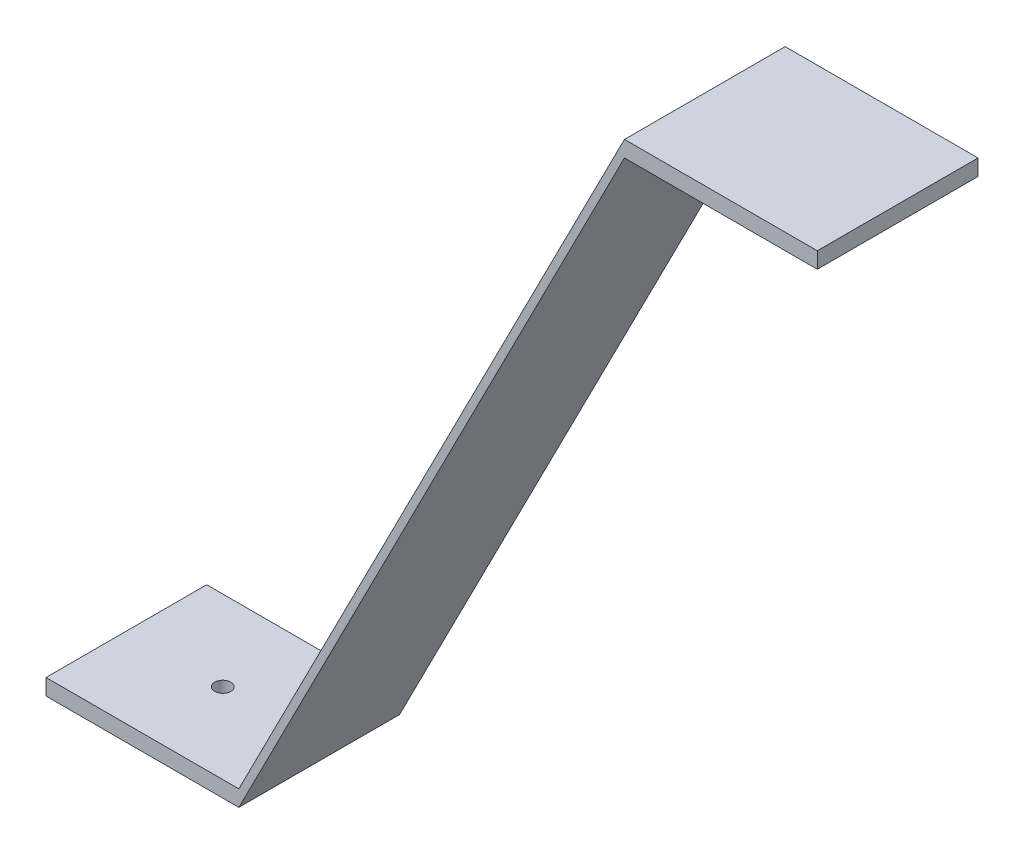
SolidWorks part; units mm, degrees
ref_plane "Front Plane" through (0, 0, 0) normal (0, 0, 1) x (1, 0, 0)
ref_plane "Top Plane" through (0, 0, 0) normal (0, 1, 0) x (1, 0, 0)
ref_plane "Right Plane" through (0, 0, 0) normal (1, 0, 0) x (0, 0, -1)
sketch "Sketch1" plane through (0, 0, 0) normal (0, 1, 0) x (1, 0, 0)
  line L1 (-38.1, -31.75) -> (38.1, -31.75)
  line L2 (-38.1, -31.75) -> (-38.1, 31.75)
  line L3 (-38.1, 31.75) -> (38.1, 31.75)
  line L4 (38.1, -31.75) -> (38.1, 31.75)
  line L5 (-38.1, -31.75) -> (38.1, 31.75) construction
  line L6 (-38.1, 31.75) -> (38.1, -31.75) construction
  point P0 (0, 0)
  dimension "D1" = 76.2
  dimension "D2" = 63.5
extrude "Boss-Extrude1" add sketch "Sketch1" along normal blind 6.35
sketch "Sketch2" plane through (0, 6.35, 0) normal (0, 1, 0) x (1, 0, 0)
  circle A0 centre (0, 0) radius 3.175
  dimension "D1" = 6.35
extrude "Cut-Extrude1" cut sketch "Sketch2" against normal through all
ref_plane "Plane1" through (190.5, 0, 0) normal (1, 0, 0) x (0, 0, -1)
sketch "Sketch3" plane through (0, 0, 31.75) normal (0, 0, 1) x (1, 0, 0)
  line L0 (38.1, 6.35) -> (190.5, 304.8)
  line L1 (38.1, 0) -> (190.5, 298.45)
  line L2 (190.5, -3.4925) -> (190.5, 3.4925) construction
  line L3 (-38.1, 0) -> (38.1, 0) construction
  line L4 (38.1, 6.35) -> (38.1, 0)
  line L5 (190.5, 304.8) -> (190.5, 298.45)
  dimension "D1" = 304.8
extrude "Boss-Extrude2" add sketch "Sketch3" against normal blind 63.5
sketch "Sketch4" plane through (190.5, 0, 0) normal (1, 0, 0) x (0, 0, -1)
  line L1 (-31.75, 304.8) -> (31.75, 304.8)
  line L2 (-31.75, 304.8) -> (-31.75, 298.45)
  line L3 (-31.75, 298.45) -> (31.75, 298.45)
  line L4 (31.75, 304.8) -> (31.75, 298.45)
extrude "Boss-Extrude3" add sketch "Sketch4" along normal blind 76.2
